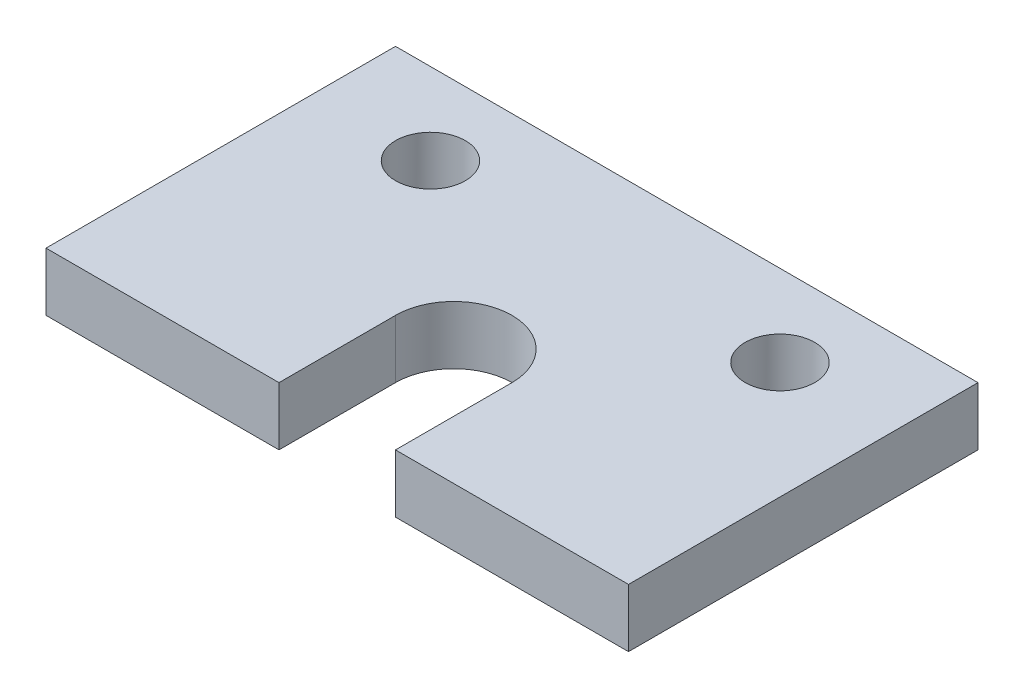
SolidWorks part; units mm, degrees
ref_plane "Front Plane" through (0, 0, 0) normal (0, 0, 1) x (1, 0, 0)
ref_plane "Top Plane" through (0, 0, 0) normal (0, 1, 0) x (1, 0, 0)
ref_plane "Right Plane" through (0, 0, 0) normal (1, 0, 0) x (0, 0, -1)
sketch "Sketch1" plane through (0, 0, 0) normal (0, 1, 0) x (1, 0, 0)
  line L1 (-15.875, -9.525) -> (15.875, -9.525)
  line L2 (-15.875, -9.525) -> (-15.875, 9.525)
  line L3 (-15.875, 9.525) -> (15.875, 9.525)
  line L4 (15.875, -9.525) -> (15.875, 9.525)
  line L5 (-15.875, -9.525) -> (15.875, 9.525) construction
  line L6 (-15.875, 9.525) -> (15.875, -9.525) construction
  point P0 (0, 0)
  dimension "D1" = 19.05
  dimension "D2" = 31.75
extrude "Boss-Extrude1" add sketch "Sketch1" along normal blind 3.175
sketch "Sketch2" plane through (0, 3.175, 0) normal (0, 1, 0) x (1, 0, 0)
  line L0 (0, -55) -> (0, 55) construction
  line L1 (-55, 0) -> (55, 0) construction
  line L2 (-3.175, -3.175) -> (-3.175, -9.525)
  line L3 (-15.875, -9.525) -> (15.875, -9.525) construction
  line L4 (-3.175, -9.525) -> (3.175, -9.525)
  line L5 (3.175, -9.525) -> (3.175, -3.175)
  arc A0 (3.175, -3.175) -> (-3.175, -3.175) centre (0, -3.175) ccw
  dimension "D1" = 6.35
extrude "Cut-Extrude1" cut sketch "Sketch2" against normal through all
sketch "Sketch3" plane through (0, 3.175, 0) normal (0, 1, 0) x (1, 0, 0)
  line L0 (-9.525, 5.08) -> (9.525, 5.08) construction
  line L1 (0, -1.7463) -> (0, 1.7463) construction
  line L2 (-1.7463, 0) -> (1.7463, 0) construction
  point P0 (-9.525, 5.08)
  point P1 (9.525, 5.08)
  point P4 (0, 5.08)
  dimension "D1" = 19.05
  dimension "D2" = 5.08
hole_wizard "#6 Clearance Hole1" positions "Sketch4" profile "Sketch5" hole size "#6" standard "ANSI Inch" end condition up to next
sketch "Sketch4" plane through (0, 3.175, 0) normal (0, 1, 0) x (1, 0, 0)
  point P0 (-9.525, 5.08)
  point P3 (9.525, 5.08)
sketch "Sketch5" plane through (-9.525, 3.175, -5.08) normal (1, 0, 0) x (0, 0, 1)
  line L0 (0, 0) -> (0, 3.175)
  line L1 (0, 3.175) -> (1.8986, 3.175)
  line L2 (1.8986, 3.175) -> (1.8986, 0)
  line L5 (1.8986, 0) -> (0, 0)
  line L11 (0, -6.35) -> (0, 107.95) construction
  dimension "Thru Hole Dia." = 3.7973
  dimension "Thru Hole Depth" = 3.175
